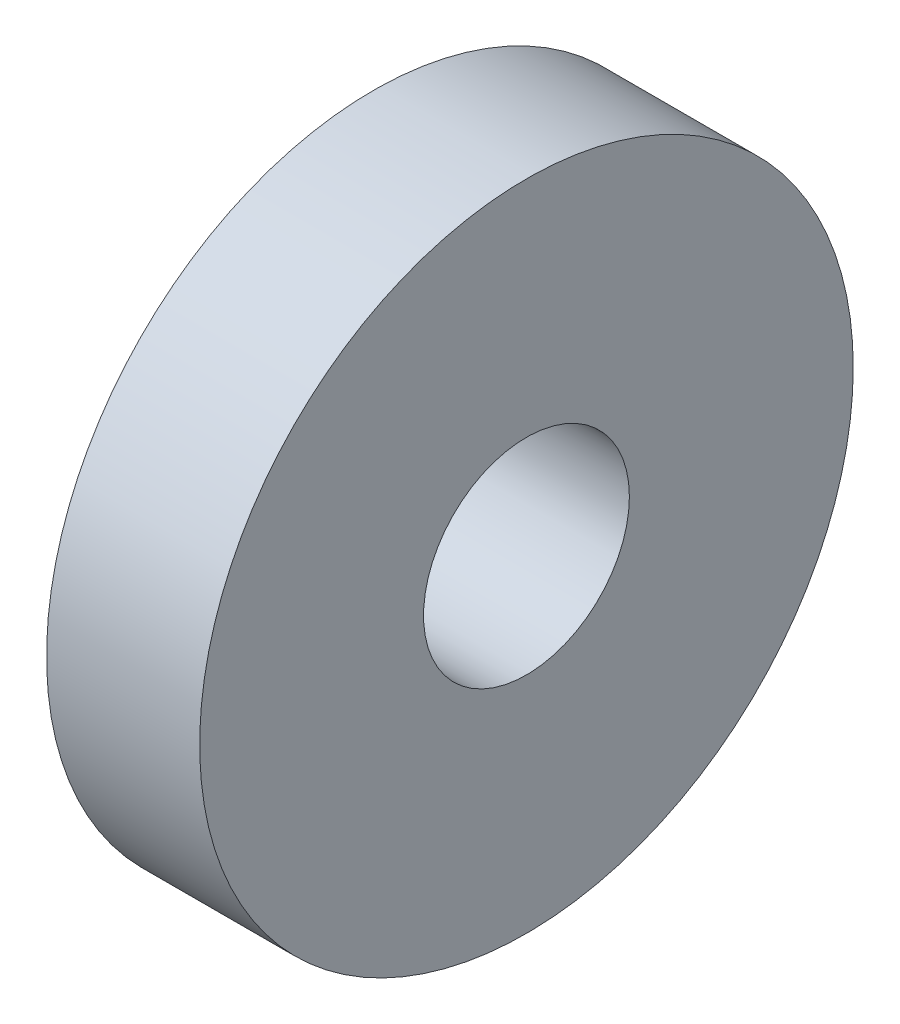
SolidWorks part; units mm, degrees
material "PET"
ref_plane "Front Plane" through (0, 0, 0) normal (0, 0, 1) x (1, 0, 0)
ref_plane "Top Plane" through (0, 0, 0) normal (0, 1, 0) x (1, 0, 0)
ref_plane "Right Plane" through (0, 0, 0) normal (1, 0, 0) x (0, 0, -1)
sketch "Sketch1" plane through (0, 0, 0) normal (1, 0, 0) x (0, 0, -1)
  circle A0 centre (0, 0) radius 6.35
  circle A1 centre (0, 0) radius 2
  dimension "D1" = 12.7
extrude "Boss-Extrude1" add sketch "Sketch1" along normal blind 2.975
